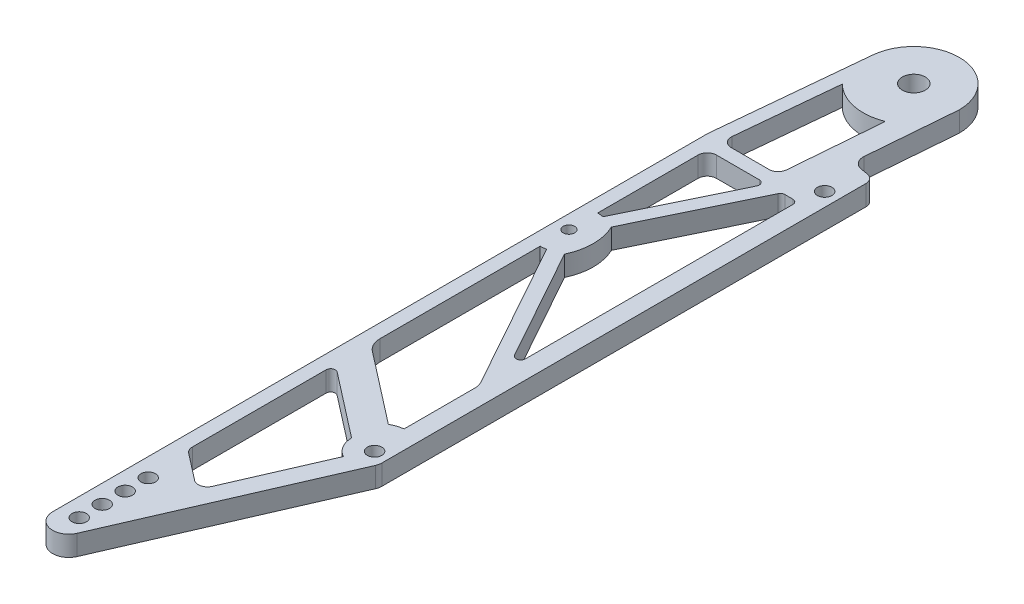
SolidWorks part; units mm, degrees
material "6061-T6 (SS)"
ref_plane "X-Y Datum" through (0, 0, 0) normal (0, 0, 1) x (1, 0, 0)
ref_plane "X-Z Datum" through (0, 0, 0) normal (0, 1, 0) x (1, 0, 0)
ref_plane "Y-Z Datum" through (0, 0, 0) normal (1, 0, 0) x (0, 0, -1)
other "Graphic1" [suppressed]
other "Graphic (Closed) -1" [suppressed]
sketch "Sketch2" plane through (0, 0, 0) normal (0, 1, 0) x (1, 0, 0)
  line L5 (13.4859, -162.4108) -> (-11.43, -143.082) construction
  line L8 (0, 0) -> (0, -24.13) construction
  line L11 (15.1556, -28.0184) -> (13.2387, -27.713)
  line L15 (-16.51, -221.3289) -> (-16.51, -40.4661)
  line L22 (-7.9887, -223.1013) -> (16.9799, -165.6775)
  line L23 (17.2959, -164.1583) -> (17.2959, -30.5268)
  line L33 (10.4385, -167.9818) -> (-0.5342, -193.2173)
  line L44 (-7.4473, -76.0744) -> (7.5755, -45.0536)
  line L45 (8.7185, -44.3372) -> (10.9459, -44.3372)
  line L46 (12.2159, -45.6072) -> (12.2159, -119.4928)
  line L47 (9.8359, -120.11) -> (-7.4473, -89.0256)
  line L49 (-12.4315, -37.7433) -> (-9.7554, -9.9996)
  line L51 (5.1277, -12.9949) -> (3.0693, -38.194)
  line L53 (0.5377, -40.5272) -> (-9.9032, -40.5272)
  line L56 (1.663, -44.3372) -> (-10.16, -44.3372)
  line L57 (13.7382, -24.5776) -> (0, 0) construction
  line L58 (10.5738, -24.3191) -> (12.5603, 0)
  line L59 (-12.7, -149.6154) -> (-12.7, -186.5441)
  line L63 (7.1359, -162.4108) -> (-10.6516, -148.612)
  line L64 (-12.7, -74.6125) -> (-12.7, -46.8772)
  line L65 (2.8061, -46.1607) -> (-11.056, -74.7846)
  line L66 (-16.4983, -40.2222) -> (-12.5023, 1.2059)
  line L67 (-4.4204, -194.2114) -> (-11.7169, -188.551)
  line L68 (5.8058, -44.3372) -> (-12.7, -82.55) construction
  line L69 (-1.7326, -64.2739) -> (-5.1616, -62.6133) construction
  line L70 (8.9236, -154.0495) -> (-10.7338, -138.8001)
  line L71 (12.2159, -152.9708) -> (12.2159, -133.548)
  line L72 (11.5758, -131.0794) -> (-11.086, -90.3217)
  line L75 (-12.7, -134.7862) -> (-12.7, -90.4875)
  circle A0 centre (0, 0) radius 3.175
  circle A2 centre (-11.43, -219.075) radius 2
  circle A3 centre (-11.43, -212.725) radius 2
  circle A4 centre (-11.43, -206.375) radius 2
  circle A5 centre (-11.43, -200.025) radius 2
  circle A7 centre (0, 0) radius 12.5603 construction
  circle A8 centre (-12.7, -82.55) radius 1.5875
  circle A12 centre (13.4859, -38.1) radius 2
  arc A13 (-12.5023, 1.2059) -> (12.5603, 0) centre (0, 0) cw
  arc A14 (-7.4473, -89.0256) -> (-7.4473, -76.0744) centre (-20.962, -82.55) ccw
  circle A16 centre (24.0125, -14.7036) radius 3.175 construction
  arc A17 (24.0125, -14.7036) -> (13.7382, -24.5776) centre (0, 0) cw construction
  circle A18 centre (13.7382, -24.5776) radius 3.175 construction
  arc A19 (13.2387, -27.713) -> (10.5738, -24.3191) centre (13.7382, -24.5776) cw
  arc A20 (15.1556, -28.0184) -> (17.2959, -30.5268) centre (14.7559, -30.5268) cw
  circle A21 centre (13.4859, -162.4108) radius 2
  arc A24 (10.4385, -167.9818) -> (7.1359, -162.4108) centre (13.4859, -162.4108) cw
  arc A25 (-16.51, -221.3289) -> (-7.9887, -223.1013) centre (-12.065, -221.3289) ccw
  arc A26 (-12.7, -74.6125) -> (-11.056, -74.7846) centre (-12.7, -82.55) cw
  arc A28 (5.1277, -12.9949) -> (-9.7554, -9.9996) centre (0, 0) cw
  arc A31 (-10.16, -44.3372) -> (-12.7, -46.8772) centre (-10.16, -46.8772) ccw
  arc A32 (-12.4315, -37.7433) -> (-9.9032, -40.5272) centre (-9.9032, -37.9872) ccw
  arc A33 (0.5377, -40.5272) -> (3.0693, -38.194) centre (0.5377, -37.9872) ccw
  arc A36 (-12.7, -149.6154) -> (-10.6516, -148.612) centre (-11.43, -149.6154) cw
  arc A37 (9.8359, -120.11) -> (12.2159, -119.4928) centre (10.9459, -119.4928) ccw
  arc A38 (7.5755, -45.0536) -> (8.7185, -44.3372) centre (8.7185, -45.6072) cw
  arc A39 (10.9459, -44.3372) -> (12.2159, -45.6072) centre (10.9459, -45.6072) cw
  arc A40 (1.663, -44.3372) -> (2.8061, -46.1607) centre (1.663, -45.6072) cw
  arc A50 (17.2959, -164.1583) -> (16.9799, -165.6775) centre (13.4859, -164.1583) cw
  arc A52 (-16.4983, -40.2222) -> (-16.51, -40.4661) centre (-13.97, -40.4661) ccw
  arc A53 (-12.7, -186.5441) -> (-11.7169, -188.551) centre (-10.16, -186.5441) ccw
  arc A54 (-4.4204, -194.2114) -> (-0.5342, -193.2173) centre (-2.8635, -192.2045) ccw
  arc A55 (12.2159, -152.9708) -> (8.9236, -154.0495) centre (13.4859, -162.4108) ccw
  arc A56 (-11.086, -90.3217) -> (-12.7, -90.4875) centre (-12.7, -82.55) cw
  arc A57 (-12.7, -134.7862) -> (-10.7338, -138.8001) centre (-7.62, -134.7862) ccw
  arc A58 (11.5758, -131.0794) -> (12.2159, -133.548) centre (7.1359, -133.548) cw
  point P30 (17.2959, -28.3595)
  point P44 (-3.4471, -63.4436)
  point P45 (-1.8376, -196.215)
  point P48 (12.2159, -82.55)
  point P88 (-12.7, -44.3372)
  point P91 (-12.7, -40.5272)
  point P104 (12.2159, -124.3904)
  point P107 (7.9224, -44.3372)
  point P110 (12.2159, -44.3372)
  point P120 (17.2959, -164.9508)
  dimension "D1" = 6.35
  dimension "D6" = 4
  dimension "D12" = 24.13
  dimension "D5" = 25.1206
  dimension "D14" = 3.175
  dimension "D19" = 4
  dimension "D20" = 6.35
  dimension "D24" = 3.81
  dimension "D50" = 14.986
  dimension "D51" = 8.262
  dimension "D42" = 3.81
  dimension "D62" = 6.35
  dimension "D63" = 29.204
  dimension "D27" = 2.54
  dimension "D44" = 4
  dimension "D18" = 4.445
  dimension "D34" = 3.81
  dimension "D36" = 6.35
  dimension "D33" = 13.97
  dimension "D38" = 3.81
  dimension "D39" = 8.89
  dimension "D48" = 2.54
  dimension "D49" = 1.27
  dimension "D52" = 3.81
  dimension "D53" = 3.81
  dimension "D54" = 9.525
  dimension "D58" = 2.54
  dimension "D59" = 3.81
  dimension "D29" = 7.9375
  dimension "D31" = 3.81
  dimension "D41" = 2.54
  dimension "D55" = 7.9375
  dimension "D57" = 5.08
  dimension "D7" = 6.35
  dimension "D8" = 6.35
  dimension "D9" = 6.35
  dimension "D10" = 5.08
  dimension "D11" = 5.08
  dimension "D13" = 4.1084
  dimension "D15" = 82.55
  dimension "D16" = 12.7
  dimension "D17" = 13.7382
  dimension "D21" = 136.5913
  dimension "D22" = 38.1
  dimension "D23" = 13.4859
  dimension "D25" = 5.08
  dimension "D26" = 3.81
  dimension "D28" = 40.5272
  dimension "D30" = 2.54
  dimension "D32" = 3.81
  dimension "D35" = 3.81
  dimension "D37" = 16.51
  dimension "D40" = 23.5
  dimension "D43" = 200.025
  dimension "D45" = 6.35
  dimension "D46" = 6.35
  dimension "D47" = 4.2935
  dimension "D56" = 3.81
  dimension "D60" = 24.0125
  dimension "D61" = 14.7036
extrude "Boss-Extrude1" add sketch "Sketch2" along normal blind 5.588
sketch "Sketch4" plane through (0, 5.588, 0) normal (0, 1, 0) x (1, 0, 0)
  line L0 (0, 0) -> (0, -29.0331) construction
sketch "Sketch6" plane through (-16.51, 0, 0) normal (-1, 0, 0) x (0, 0, 1)
  line L0 (183.2289, 5.588) -> (183.2289, 0)
  line L1 (40.4661, 5.588) -> (221.3289, 5.588) construction
  line L2 (40.4661, 0) -> (221.3289, 0) construction
  line L3 (221.3289, 5.588) -> (221.3289, 0) construction
  dimension "D1" = 38.1
split line "Split Line2"
